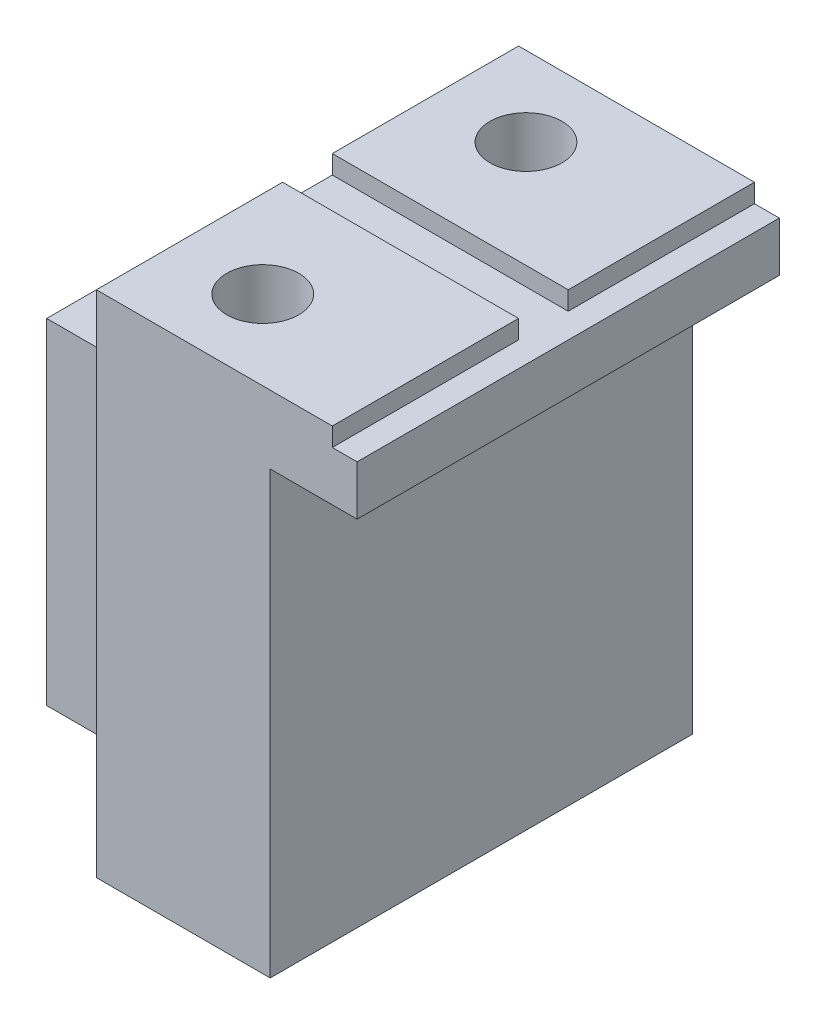
SolidWorks part; units mm, degrees
ref_plane "Alzado" through (0, 0, 0) normal (0, 0, 1) x (1, 0, 0)
ref_plane "Planta" through (0, 0, 0) normal (0, 1, 0) x (1, 0, 0)
ref_plane "Vista lateral" through (0, 0, 0) normal (1, 0, 0) x (0, 0, -1)
sketch "Croquis1" plane through (0, 0, 0) normal (0, 0, 1) x (1, 0, 0)
  line L0 (10.5, 15.75) -> (10.5, 16.25) construction
  line L1 (0, 0) -> (4, 0)
  line L2 (0, 9.5) -> (0, 16.5)
  line L4 (7, 0) -> (7, 13.75)
  line L9 (9.5, 15.75) -> (10.5, 15.75)
  line L12 (10.5, 15.75) -> (10.5, 13.75)
  line L13 (10.5, 16) -> (7, 16) construction
  line L15 (7, 13.75) -> (7, 16.5) construction
  line L16 (0, 9.5) -> (0, 0) construction
  line L17 (3.5, 0) -> (3.5, 16.5) construction
  line L18 (7, 16.5) -> (0, 16.5)
  line L21 (7, 16.5) -> (9.5, 16.5)
  line L22 (9.5, 15.75) -> (9.5, 16.5)
  line L25 (7, 13.75) -> (10.5, 13.75)
  line L27 (0, 0) -> (-7, 0)
  line L29 (0, 9.5) -> (-7, 9.5)
  line L30 (-7, 0) -> (-7, 9.5)
  line L31 (-3.5, 9.5) -> (-3.5, 0) construction
  line L32 (4, 0) -> (7, 0) construction
  line L34 (7, 0) -> (7, -4)
  line L35 (7, -4) -> (4, -4)
  line L36 (4, 0) -> (4, -4)
  line L37 (0, 13) -> (3.5, 13) construction
  line L38 (3.5, 13) -> (7, 13) construction
  dimension "D1" = 16.5
  dimension "D2" = 7
  dimension "D3" = 0.5
  dimension "D4" = 16
  dimension "D5" = 2
  dimension "D6" = 7
  dimension "D7" = 1
  dimension "D8" = 9.5
  dimension "D9" = 7
  dimension "D10" = 7.5
  dimension "D11" = 4
extrude "Saliente-Extruir1" add sketch "Croquis1" along normal blind 7
sketch "Croquis5" plane through (0, 9.5, 0) normal (0, 1, 0) x (1, 0, 0)
  line L0 (-7, 0) -> (0, -7) construction
  circle A0 centre (-3.5, -3.5) radius 1.6
  dimension "D1" = 3.2
extrude "Cortar-Extruir2" cut sketch "Croquis5" against normal blind 13.9
sketch "Croquis6" plane through (0, 9.5, 0) normal (0, 1, 0) x (1, 0, 0)
  circle A0 centre (-3.5, -3.5) radius 2.75
  dimension "D1" = 5.5
extrude "Cortar-Extruir3" cut sketch "Croquis6" against normal blind 3
sketch "Croquis7" plane through (0, 0, 7) normal (0, 0, 1) x (1, 0, 0)
  line L0 (7, -4) -> (7, 13.75) construction
  line L2 (0, 16.5) -> (0, 0)
  line L3 (0, 0) -> (7, 0)
  line L4 (7, 13.75) -> (7, 0)
  line L5 (-7, 0) -> (4, 0) construction
  line L6 (9.5, 16.5) -> (0, 16.5) construction
  line L7 (9.5, 15.75) -> (9.5, 16.5) construction
  line L8 (10.5, 15.75) -> (9.5, 15.75) construction
  line L9 (10.5, 13.75) -> (10.5, 15.75) construction
  line L10 (7, 13.75) -> (10.5, 13.75) construction
  line L11 (9.5, 16.5) -> (0, 16.5)
  line L12 (9.5, 15.75) -> (9.5, 16.5)
  line L13 (10.5, 15.75) -> (9.5, 15.75)
  line L14 (10.5, 13.75) -> (10.5, 15.75)
  line L15 (7, 13.75) -> (10.5, 13.75)
extrude "Saliente-Extruir2" add sketch "Croquis7" along normal blind 5 and the other way blind 12
sketch "Croquis8" plane through (0, 16.5, 0) normal (0, 1, 0) x (1, 0, 0)
  line L0 (0, -3.5) -> (7, -3.5) construction
  line L3 (3.5, -12) -> (3.5, 5) construction
  line L4 (9.5, -12) -> (0, -12) construction
  line L5 (9.5, 5) -> (0, 5) construction
  line L6 (0, -12) -> (0, 5) construction
  line L7 (7, -12) -> (7, 5) construction
  circle A0 centre (3.5, 1.8) radius 1.45
  circle A1 centre (3.5, -8.8) radius 1.45
  point P12 (3.5, -3.5)
  dimension "D1" = 2.9
  dimension "D2" = 3.2
extrude "Cortar-Extruir4" cut sketch "Croquis8" against normal blind 10
sketch "Croquis9" plane through (9.5, 0, 0) normal (1, 0, 0) x (0, 0, -1)
  line L0 (-12, 15.75) -> (5, 15.75) construction
  line L1 (-4.5, 15.75) -> (-2.5, 15.75)
  line L2 (-4.5, 15.75) -> (-4.5, 16.5)
  line L3 (-4.5, 16.5) -> (-2.5, 16.5)
  line L4 (-2.5, 15.75) -> (-2.5, 16.5)
  line L5 (-12, 16.5) -> (5, 16.5) construction
  line L6 (-3.5, 15.75) -> (-3.5, -4) construction
  line L7 (-7, -4) -> (0, -4) construction
  dimension "D1" = 2
extrude "Cortar-Extruir5" cut sketch "Croquis9" against normal blind 10
sketch "Croquis10" plane through (0, 0, 0) normal (0, -1, 0) x (1, 0, 0)
  line L12 (-7, 0) -> (0, 0)
  line L13 (0, 0) -> (0, -5)
  line L14 (0, -5) -> (7, -5)
  line L15 (7, -5) -> (7, 0)
  line L16 (7, 0) -> (4, 0)
  line L17 (4, 0) -> (4, 7)
  line L18 (4, 7) -> (7, 7)
  line L19 (7, 7) -> (7, 12)
  line L20 (7, 12) -> (0, 12)
  line L21 (0, 12) -> (0, 7)
  line L22 (0, 7) -> (-7, 7)
  line L23 (-7, 7) -> (-7, 0)
  line L24 (-7, 0) -> (0, 0)
  line L25 (0, 0) -> (0, -5)
  line L26 (0, -5) -> (7, -5)
  line L27 (7, -5) -> (7, 0)
  line L28 (7, 0) -> (4, 0)
  line L29 (4, 0) -> (4, 7)
  line L30 (4, 7) -> (7, 7)
  line L31 (7, 7) -> (7, 12)
  line L32 (7, 12) -> (0, 12)
  line L33 (0, 12) -> (0, 7)
  line L34 (0, 7) -> (-7, 7)
  line L35 (-7, 7) -> (-7, 0)
  circle A0 centre (-3.5, 3.5) radius 1.6 construction
  circle A1 centre (-3.5, 3.5) radius 1.6
  dimension "D1" = 0
extrude "Saliente-Extruir3" add sketch "Croquis10" along normal up to surface (4 mm away) up to face at (5.5, -4, 3.5)
